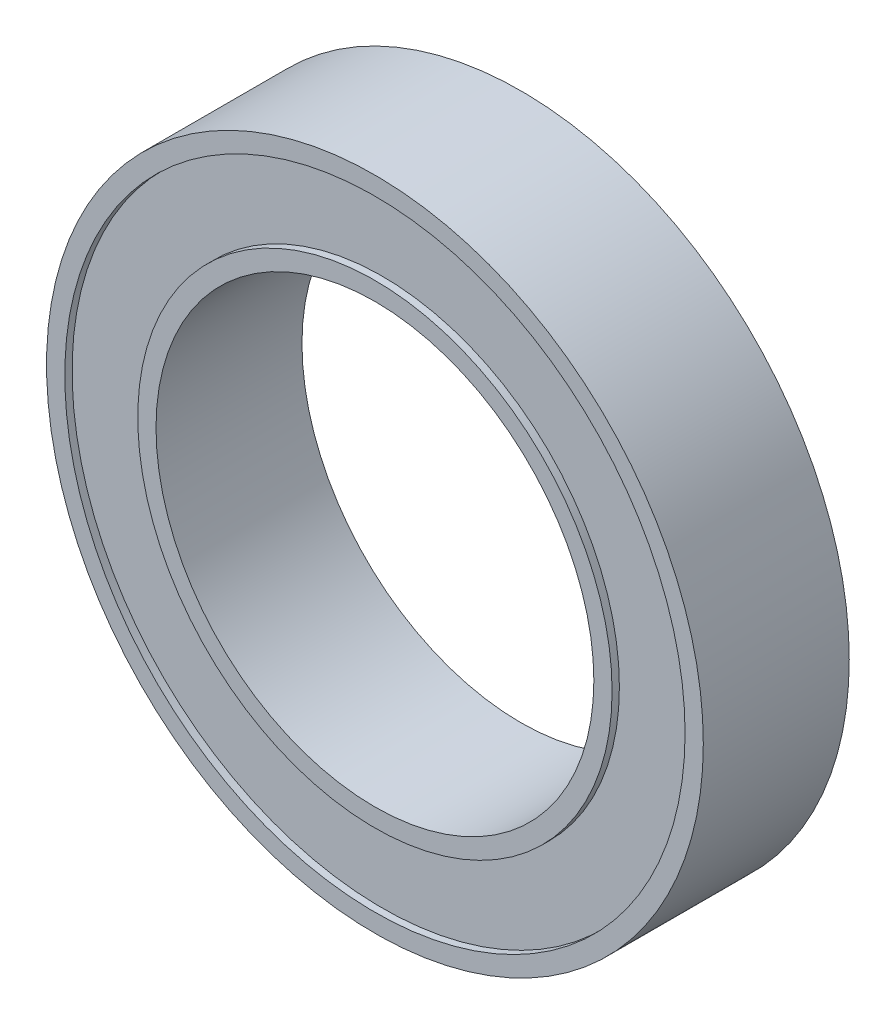
SolidWorks part; units mm, degrees
ref_plane "Front Plane" through (0, 0, 0) normal (0, 0, 1) x (1, 0, 0)
ref_plane "Top Plane" through (0, 0, 0) normal (0, 1, 0) x (1, 0, 0)
ref_plane "Right Plane" through (0, 0, 0) normal (1, 0, 0) x (0, 0, -1)
ref_plane "Plane1"
sketch "Sketch1" plane through (0, 0, 0) normal (0, 0, 1) x (1, 0, 0)
  circle A0 centre (0, 0) radius 9
  circle A1 centre (0, 0) radius 8.5
  circle A2 centre (0, 0) radius 6.5
  circle A3 centre (0, 0) radius 6
  dimension "D1" = 18
  dimension "D2" = 12
extrude "Extrusion1" add sketch "Sketch1" along normal blind 4 contours A2 A3 | A0 A1
ref_plane "Plane2"
sketch "Sketch2" plane through (0, 0, 0.2) normal (0, 0, 1) x (1, 0, 0)
  circle A0 centre (0, 0) radius 8.5
  circle A1 centre (0, 0) radius 6.5
extrude "Extrusion2" add sketch "Sketch2" along normal blind 3.6 contours A0 A1
